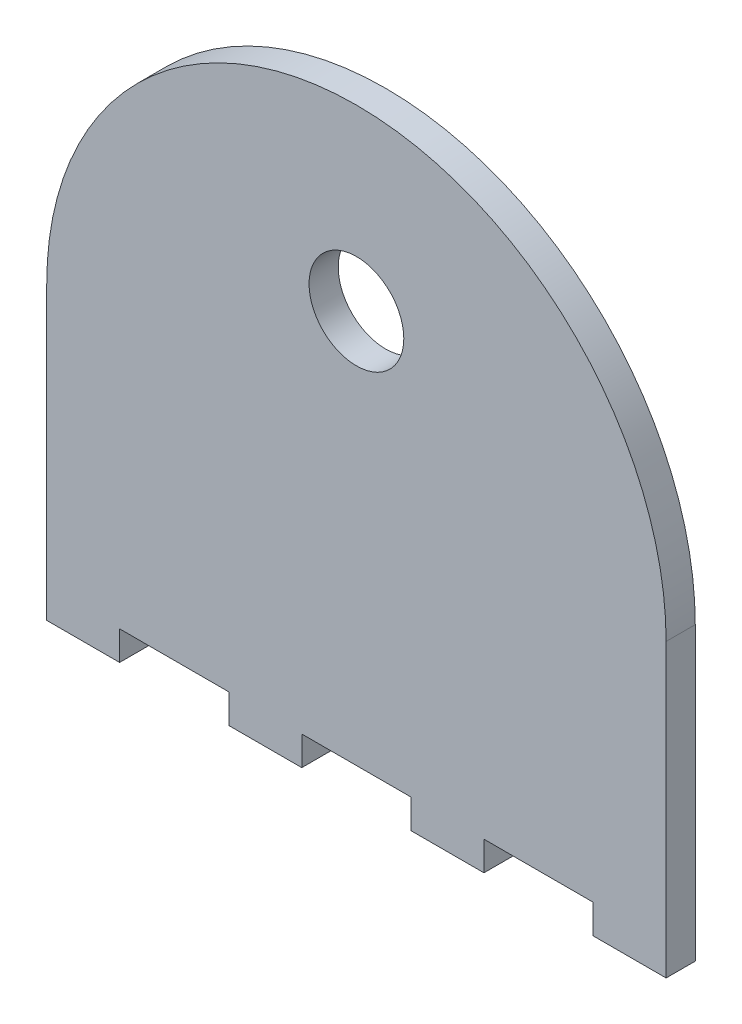
SolidWorks part; units mm, degrees
ref_plane "Alzado" through (0, 0, 0) normal (0, 0, 1) x (1, 0, 0)
ref_plane "Planta" through (0, 0, 0) normal (0, 1, 0) x (1, 0, 0)
ref_plane "Vista lateral" through (0, 0, 0) normal (1, 0, 0) x (0, 0, -1)
sketch "Croquis1" plane through (0, 0, 0) normal (0, 0, 1) x (1, 0, 0)
  line L0 (0, 0) -> (10, 0)
  line L1 (10, 0) -> (10, 4)
  line L2 (10, 4) -> (25, 4)
  line L3 (25, 4) -> (25, 0)
  line L4 (25, 0) -> (35, 0)
  line L5 (35, 0) -> (35, 4)
  line L6 (35, 4) -> (50, 4)
  line L7 (50, 4) -> (50, 0)
  line L8 (50, 0) -> (60, 0)
  line L9 (60, 0) -> (60, 4)
  line L10 (60, 4) -> (75, 4)
  line L11 (75, 4) -> (75, 0)
  line L12 (75, 0) -> (85, 0)
  line L13 (85, 0) -> (85, 40)
  line L14 (0, 0) -> (0, 40)
  line L15 (0, 40) -> (85, 40) construction
  line L16 (42.5, 40) -> (42.5, 53.8096) construction
  arc A0 (0, 40) -> (85, 40) centre (42.5, 40) cw
  dimension "D1" = 40
  dimension "D2" = 4
  dimension "D3" = 15
  dimension "D6" = 10
extrude "Saliente-Extruir1" add sketch "Croquis1" along normal blind 4
sketch "Croquis2" plane through (0, 0, 4) normal (0, 0, 1) x (1, 0, 0)
  line L0 (0, 0) -> (0, 40) construction
  circle A0 centre (42.5, 58) radius 6.5
  arc A1 (85, 40) -> (0, 40) centre (42.5, 40) ccw construction
  dimension "D1" = 13
  dimension "D2" = 18
  dimension "D3" = 42.5
extrude "Cortar-Extruir1" cut sketch "Croquis2" against normal blind 4
